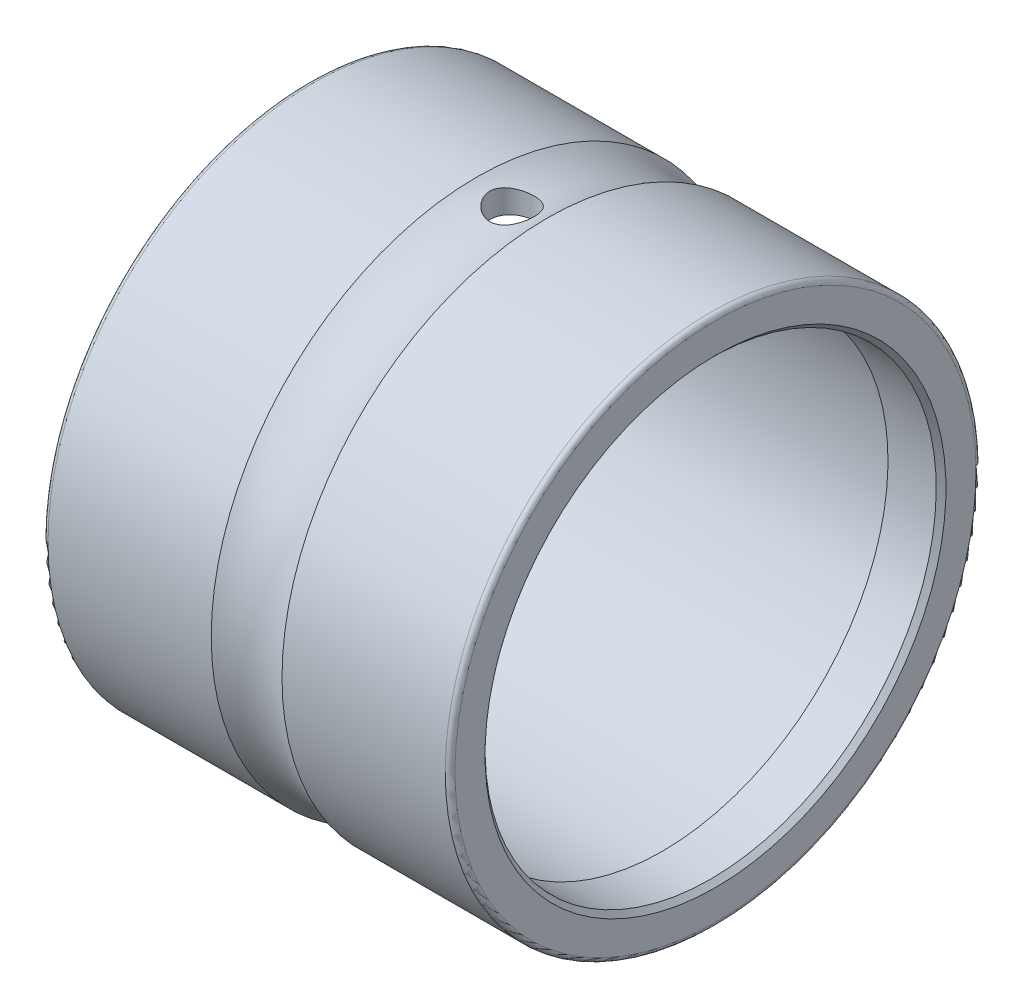
SolidWorks part; units mm, degrees
material "1023 Carbon Steel Sheet (SS)"
ref_plane "Front Plane" through (0, 0, 0) normal (0, 0, 1) x (1, 0, 0)
ref_plane "Top Plane" through (0, 0, 0) normal (0, 1, 0) x (1, 0, 0)
ref_plane "Right Plane" through (0, 0, 0) normal (1, 0, 0) x (0, 0, -1)
sketch "Sketch2" plane through (0, 0, 0) normal (0, 0, 1) x (1, 0, 0)
  line L0 (-11.5, 0) -> (11.5, 0) construction
  line L1 (-11.5, 15) -> (-2, 15) construction
  line L2 (0, 0) -> (0, 15) construction
  line L3 (-11.5, 12.75) -> (11.5, 12.75) construction
  line L4 (-11.5, 13.3) -> (11.5, 13.3) construction
  line L5 (8.5, 15) -> (8.5, 12.75) construction
  line L6 (-8.5, 13.3) -> (8.5, 13.3)
  line L7 (8.5, 13.3) -> (8.5, 12.75)
  line L8 (8.5, 12.75) -> (11.225, 12.75)
  line L9 (11.5, 13.025) -> (11.5, 15) construction
  line L10 (11.225, 12.75) -> (11.5, 13.025)
  line L11 (11.5, 13.025) -> (11.5, 14.725)
  line L12 (-11.225, 15) -> (-2, 15)
  line L13 (-8.5, 13.3) -> (-8.5, 12.75)
  line L14 (-8.5, 12.75) -> (-11.225, 12.75)
  line L15 (-11.225, 12.75) -> (-11.5, 13.025)
  line L16 (-11.5, 13.025) -> (-11.5, 14.725)
  line L18 (2, 15) -> (11.5, 15) construction
  line L19 (-11.5, 15) -> (11.5, 15) construction
  line L20 (2, 15) -> (11.225, 15)
  arc A0 (11.5, 14.725) -> (11.225, 15) centre (11.225, 14.725) ccw
  arc A1 (-11.5, 14.725) -> (-11.225, 15) centre (-11.225, 14.725) cw
  arc A2 (-2, 15) -> (2, 15) centre (0, 18.75) ccw
  point P2 (0, 0)
  point P20 (0, 13.3)
  point P32 (0, 14.5)
  dimension "D6" = 0.55
  dimension "D1" = 23
  dimension "D2" = 15
  dimension "D5" = 3
  dimension "D7" = 4
  dimension "D8" = 0.5
  dimension "D3" = 2.25
  dimension "D4" = 1.7
revolve "Revolve1" add sketch "Sketch2" angle 360 about L0
sketch "Sketch3" plane through (0, 0, 0) normal (1, 0, 0) x (0, 0, -1)
  circle A0 centre (0, 0) radius 11 construction
  circle A1 centre (0, 0) radius 13.3 construction
  circle A2 centre (0, 0) radius 13.3 construction
  dimension "D1" = 22
  dimension "D2" = 2.3
sketch "Sketch4" plane through (0, 0, 0) normal (0, 1, 0) x (1, 0, 0)
  circle A0 centre (0, 0) radius 1.25
  dimension "D1" = 2.5
extrude "Cut-Extrude1" cut sketch "Sketch4" along normal through all
